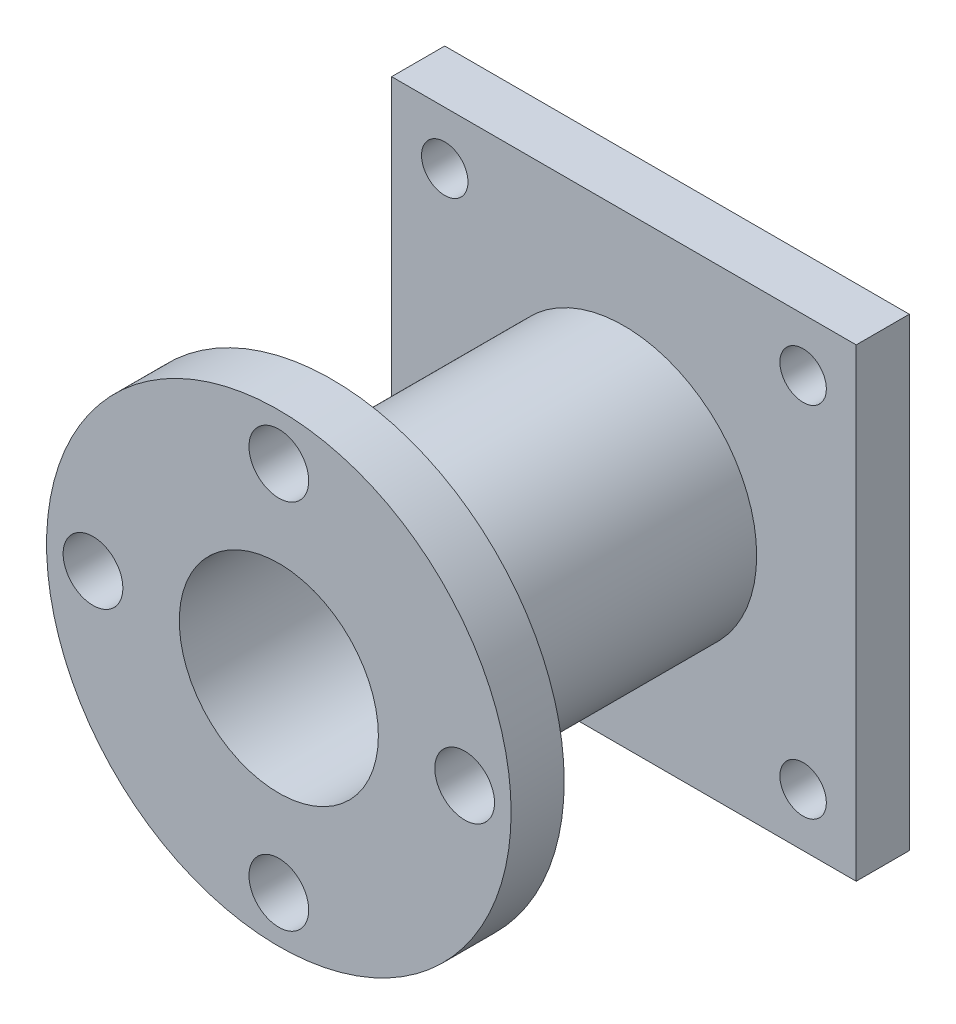
SolidWorks part; units mm, degrees
ref_plane "前视基准面" through (0, 0, 0) normal (0, 0, 1) x (1, 0, 0)
ref_plane "上视基准面" through (0, 0, 0) normal (0, 1, 0) x (1, 0, 0)
ref_plane "右视基准面" through (0, 0, 0) normal (1, 0, 0) x (0, 0, -1)
sketch "草图1" plane through (0, 0, 0) normal (0, 0, 1) x (1, 0, 0)
  circle A0 centre (0, 0) radius 20
extrude "凸台-拉伸1" add sketch "草图1" along normal blind 60
sketch "草图2" plane through (0, 0, 0) normal (0, 0, 1) x (1, 0, 0)
  line L0 (-35, -35) -> (35, -35)
  line L1 (35, -35) -> (35, 35)
  line L2 (35, 35) -> (-35, 35)
  line L3 (-35, 35) -> (-35, -35)
extrude "凸台-拉伸2" add sketch "草图2" along normal blind 8
ref_plane "基准面1" through (0, 0, 52) normal (0, 0, 1) x (1, 0, 0)
sketch "草图3" plane through (0, 0, 52) normal (0, 0, 1) x (1, 0, 0)
  circle A0 centre (0, 0) radius 35
extrude "凸台-拉伸3" add sketch "草图3" along normal blind 8
sketch "草图4" plane through (0, 0, 0) normal (0, 0, 1) x (1, 0, 0)
  circle A0 centre (0, 0) radius 15
extrude "切除-拉伸1" cut sketch "草图4" against normal mid plane 142
sketch "草图5" plane through (0, 0, 0) normal (0, 0, 1) x (1, 0, 0)
  circle A0 centre (27, 27) radius 3.5
  circle A1 centre (-27, 27) radius 3.5
  circle A2 centre (-27, -27) radius 3.5
  circle A3 centre (27, -27) radius 3.5
extrude "切除-拉伸2" cut sketch "草图5" along normal blind 8
ref_plane "基准面2" through (0, 0, 60) normal (0, 0, 1) x (1, 0, 0)
sketch "草图6" plane through (0, 0, 60) normal (0, 0, 1) x (1, 0, 0)
  circle A0 centre (28, 0) radius 4.5
  circle A1 centre (0, 28) radius 4.5
  circle A2 centre (-28, 0) radius 4.5
  circle A3 centre (0, -28) radius 4.5
extrude "切除-拉伸3" cut sketch "草图6" against normal blind 8
